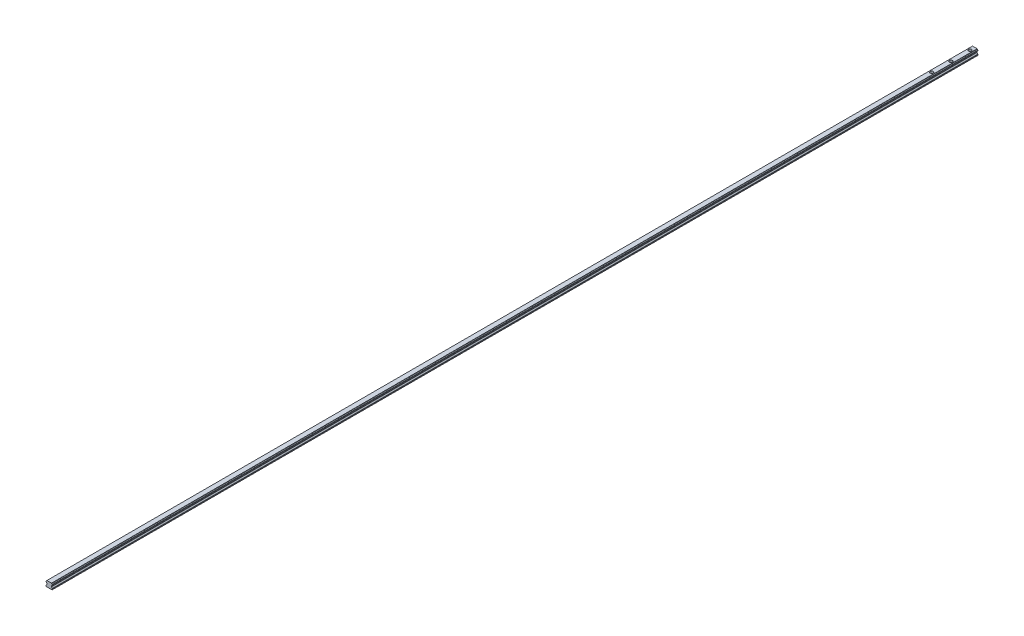
SolidWorks part; units mm, degrees
ref_plane "Piano frontale" through (0, 0, 0) normal (0, 0, 1) x (1, 0, 0)
ref_plane "Piano superiore" through (0, 0, 0) normal (0, 1, 0) x (1, 0, 0)
ref_plane "Piano destro" through (0, 0, 0) normal (1, 0, 0) x (0, 0, -1)
ref_plane "Piano1" through (0, 0, -75) normal (0, 0, -1) x (-1, 0, 0)
sketch "Schizzo1" plane through (0, 0, -75) normal (0, 0, -1) x (-1, 0, 0)
  line L0 (-7.2307, 0) -> (-10, -2.7693)
  line L1 (-10, -2.7693) -> (-10, -17.5)
  line L2 (-10, -17.5) -> (10, -17.5)
  line L3 (10, -17.5) -> (10, -2.7693)
  line L4 (10, -2.7693) -> (7.2307, 0)
  line L5 (7.2307, 0) -> (-7.2307, 0)
extrude "Estrusione-Estrusione1" add sketch "Schizzo1" against normal blind 2900
sketch "Schizzo2" plane through (0, 0, 2825) normal (0, 0, 1) x (1, 0, 0)
  line L0 (10, -4.2407) -> (6.6, -7.6407)
  line L1 (6.6, -7.6407) -> (6.6, -13.4293)
  line L2 (6.6, -13.4293) -> (10, -13.4293)
  line L3 (10, -13.4293) -> (10, -4.2407)
extrude "Taglio-Estrusione1" cut sketch "Schizzo2" against normal through all
sketch "Schizzo3" plane through (0, 0, 2825) normal (0, 0, 1) x (1, 0, 0)
  line L0 (7.7621, -6.4786) -> (9.5586, -4.6821)
  arc A0 (9.5586, -4.6821) -> (7.7621, -6.4786) centre (9.78, -6.7) ccw
extrude "Taglio-Estrusione2" cut sketch "Schizzo3" against normal up to next
sketch "Schizzo4" plane through (0, 0, 2825) normal (0, 0, 1) x (1, 0, 0)
  line L0 (-10, -13.4293) -> (-6.6, -13.4293)
  line L1 (-6.6, -13.4293) -> (-6.6, -7.6407)
  line L2 (-6.6, -7.6407) -> (-10, -4.2407)
  line L3 (-10, -4.2407) -> (-10, -13.4293)
extrude "Taglio-Estrusione3" cut sketch "Schizzo4" against normal through all
sketch "Schizzo5" plane through (0, 0, 2825) normal (0, 0, 1) x (1, 0, 0)
  line L0 (-9.5586, -4.6821) -> (-7.7621, -6.4786)
  arc A0 (-7.7621, -6.4786) -> (-9.5586, -4.6821) centre (-9.78, -6.7) ccw
extrude "Taglio-Estrusione4" cut sketch "Schizzo5" against normal through all
sketch "Schizzo6" plane through (0, 0, 2825) normal (0, 0, 1) x (1, 0, 0)
  line L0 (-7.7634, -0.5327) -> (-9.5476, -2.3169)
  arc A0 (-9.5476, -2.3169) -> (-7.7634, -0.5327) centre (-9.78, -0.3003) ccw
extrude "Taglio-Estrusione5" cut sketch "Schizzo6" against normal up to next
sketch "Schizzo7" plane through (0, 0, 2825) normal (0, 0, 1) x (1, 0, 0)
  line L0 (9.5476, -2.3169) -> (7.7634, -0.5327)
  arc A0 (7.7634, -0.5327) -> (9.5476, -2.3169) centre (9.78, -0.3003) ccw
extrude "Taglio-Estrusione6" cut sketch "Schizzo7" against normal through all
draft "Sformo1" type of draft neutral plane draft angle 45 faces to draft 1 face at (8.3, -13.4293, 1375) neutral plane through (10, -2.7693, 2825) neutral plane normal (1, 0, 0) parameters "D1"=45
draft "Sformo2" type of draft neutral plane draft angle 45 faces to draft 1 face at (-8.3, -13.4293, 1375) neutral plane through (-10, -17.5, 2825) neutral plane normal (-1, 0, 0) parameters "D1"=45
hole_wizard "Foro1" positions "Schizzo9" profile "Schizzo8" legacy
sketch "Schizzo9" plane through (0, 0, 0) normal (0, 1, 0) x (1, 0, 0)
  point P0 (0, 60)
  point P1 (0, 0)
  point P2 (0, -60)
sketch "Schizzo8" plane through (0, 0, -60) normal (1, 0, 0) x (0, 0, 1)
  line L0 (0, 0) -> (0, 17.5)
  line L1 (0, 17.5) -> (3, 17.5)
  line L2 (3, 17.5) -> (3, 8.5)
  line L3 (3, 8.5) -> (4.75, 8.5)
  line L4 (4.75, 8.5) -> (4.75, 0)
  line L5 (4.75, 0) -> (0, 0)
  line L6 (0, 110) -> (0, -10) construction
  dimension "Diameter" = 6
  dimension "Depth" = 17.5
  dimension "C-Bore Diameter" = 9.5
  dimension "C-Bore Depth" = 8.5
chamfer "Smusso1" distance 1 angle 45 2 edges at (-10, -17.5, 1375) (10, -17.5, 1375)
fillet "Raccordo1" radius 0.5 12 edges at (10, -4.2407, 1375) (-9.5586, -4.6821, 1375) (-7.7621, -6.4786, 1375) (-10, -4.2407, 1375) (10, -2.7693, 1375) (9.5586, -4.6821, 1375) (7.7621, -6.4786, 1375) (-10, -2.7693, 1375) (-9.5476, -2.3169, 1375) (-7.7634, -0.5327, 1375) (9.5476, -2.3169, 1375) (7.7634, -0.5327, 1375)
fillet "Raccordo2" radius 1 6 edges at (6.6, -10.0293, 1375) (-10, -13.4293, 1375) (-6.6, -10.0293, 1375) (-6.6, -7.6407, 1375) (10, -13.4293, 1375) (6.6, -7.6407, 1375)
